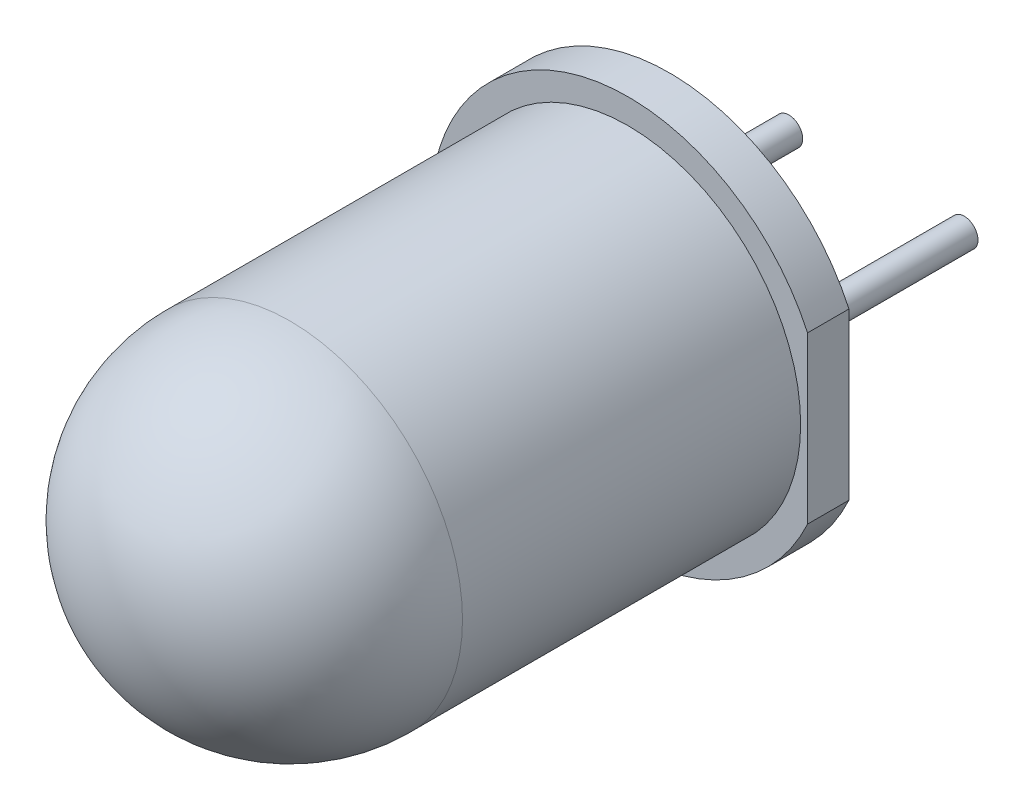
SolidWorks part; units mm, degrees
ref_plane "前视基准面" through (0, 0, 0) normal (0, 0, 1) x (1, 0, 0)
ref_plane "上视基准面" through (0, 0, 0) normal (0, 1, 0) x (1, 0, 0)
ref_plane "右视基准面" through (0, 0, 0) normal (1, 0, 0) x (0, 0, -1)
sketch "草图1" plane through (0, 0, 0) normal (0, 0, 1) x (1, 0, 0)
  line L0 (2.6, 1.2) -> (2.6, -1.2)
  arc A0 (2.6, 1.2) -> (2.6, -1.2) centre (0, 0) ccw
  circle A1 centre (0, 0) radius 2.6 construction
  dimension "D1" = 5.2
extrude "凸台-拉伸1" add sketch "草图1" along normal blind 0.6
sketch "草图2" plane through (0, 0, 0.6) normal (0, 0, 1) x (1, 0, 0)
  circle A0 centre (0, 0) radius 2.5
  dimension "D1" = 5
extrude "凸台-拉伸2" add sketch "草图2" along normal blind 7.4
fillet "圆角1" radius 2.5 1 edges at (2.5, 0, 8)
sketch "草图3" plane through (0, 0, 0) normal (0, 0, -1) x (-1, 0, 0)
  line L0 (-1.27, -2.5475) -> (-1.27, 2.6834) construction
  line L1 (0, -1000) -> (0, 49000) construction
  line L2 (-1.4702, -0.2) -> (-1.4702, 0.2) construction
  line L3 (-1000, 0) -> (49000, 0) construction
  line L4 (-1.4702, -0.2) -> (-1.0698, -0.2) construction
  line L5 (-1.4702, 0.2) -> (-1.0698, 0.2) construction
  line L6 (-1.0698, -0.2) -> (-1.0698, 0.2) construction
  line L7 (1.4702, 0.2) -> (1.0698, 0.2) construction
  line L8 (1.4702, -0.2) -> (1.4702, 0.2) construction
  line L9 (1.4702, -0.2) -> (1.0698, -0.2) construction
  line L10 (1.0698, -0.2) -> (1.0698, 0.2) construction
  line L11 (1.27, -0.2) -> (1.27, 0.2) construction
  line L12 (-1.27, -0.2) -> (-1.27, 0.2) construction
  circle A0 centre (1.27, 0) radius 0.2
  circle A1 centre (-1.27, 0) radius 0.2
  dimension "D1" = 1.27
  dimension "D2" = 0.2002
  dimension "D3" = 0.2
extrude "凸台-拉伸3" add sketch "草图3" along normal blind 3
